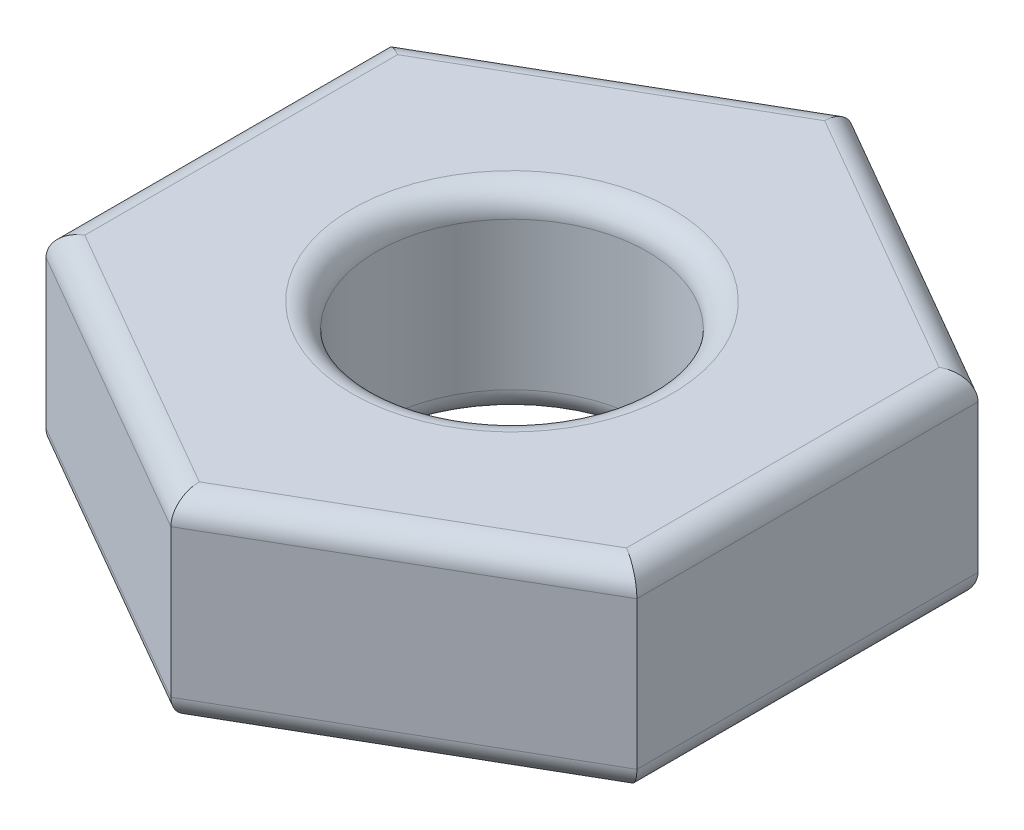
SolidWorks part; units mm, degrees
ref_plane "Front Plane" through (0, 0, 0) normal (0, 0, 1) x (1, 0, 0)
ref_plane "Top Plane" through (0, 0, 0) normal (0, 1, 0) x (1, 0, 0)
ref_plane "Right Plane" through (0, 0, 0) normal (1, 0, 0) x (0, 0, -1)
sketch "Sketch1" plane through (0, 0, 0) normal (0, 1, 0) x (1, 0, 0)
  line L1 (2.4, 1.3856) -> (0, 2.7713)
  line L2 (0, 2.7713) -> (-2.4, 1.3856)
  line L3 (-2.4, 1.3856) -> (-2.4, -1.3856)
  line L4 (-2.4, -1.3856) -> (0, -2.7713)
  line L5 (0, -2.7713) -> (2.4, -1.3856)
  line L6 (2.4, -1.3856) -> (2.4, 1.3856)
  circle A0 centre (0, 0) radius 2.4 construction
  dimension "D1" = 4.8
extrude "Boss-Extrude1" add sketch "Sketch1" along normal blind 1.6
sketch "Sketch2" plane through (0, 1.6, 0) normal (0, 1, 0) x (1, 0, 0)
  circle A0 centre (0, 0) radius 1.1
  dimension "D1" = 2.2
extrude "Cut-Extrude1" cut sketch "Sketch2" against normal up to next
fillet "Fillet1" radius 0.2 14 edges at (1.2, 0, -2.0785) (-1.2, 0, -2.0785) (-2.4, 0, 0) (-1.2, 0, 2.0785) (1.2, 0, 2.0785) (2.4, 0, 0) (0, 0, 1.1) (1.2, 1.6, 2.0785) (-1.2, 1.6, 2.0785) (-2.4, 1.6, 0) (-1.2, 1.6, -2.0785) (1.2, 1.6, -2.0785) (2.4, 1.6, 0) (0, 1.6, 1.1)
